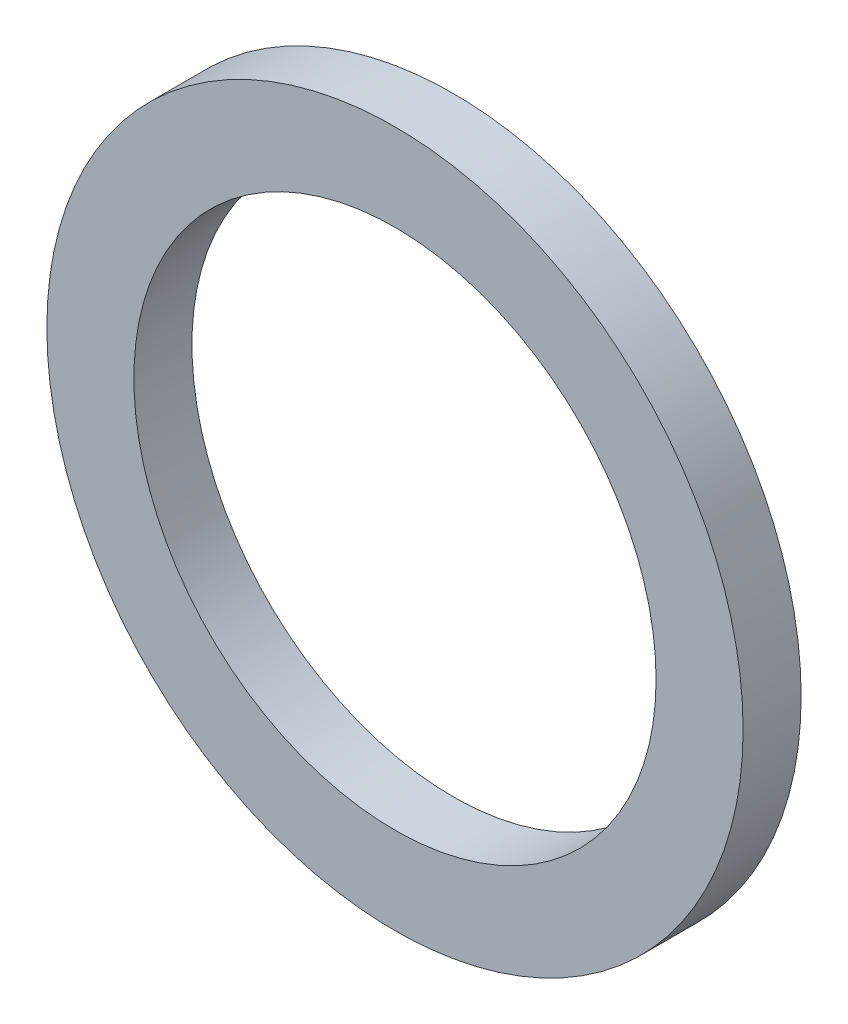
SolidWorks part; units mm, degrees
ref_plane "Front Plane" through (0, 0, 0) normal (0, 0, 1) x (1, 0, 0)
ref_plane "Top Plane" through (0, 0, 0) normal (0, 1, 0) x (1, 0, 0)
ref_plane "Right Plane" through (0, 0, 0) normal (1, 0, 0) x (0, 0, -1)
sketch "Sketch1" plane through (0, 0, 0) normal (0, 0, 1) x (1, 0, 0)
  circle A0 centre (0, 0) radius 36
  dimension "D1" = 72
extrude "Boss-Extrude1" add sketch "Sketch1" along normal blind 6
sketch "Sketch2" plane through (0, 0, 6) normal (0, 0, 1) x (1, 0, 0)
  circle A0 centre (0, 0) radius 27
  dimension "D1" = 54
extrude "Cut-Extrude1" cut sketch "Sketch2" against normal through all
